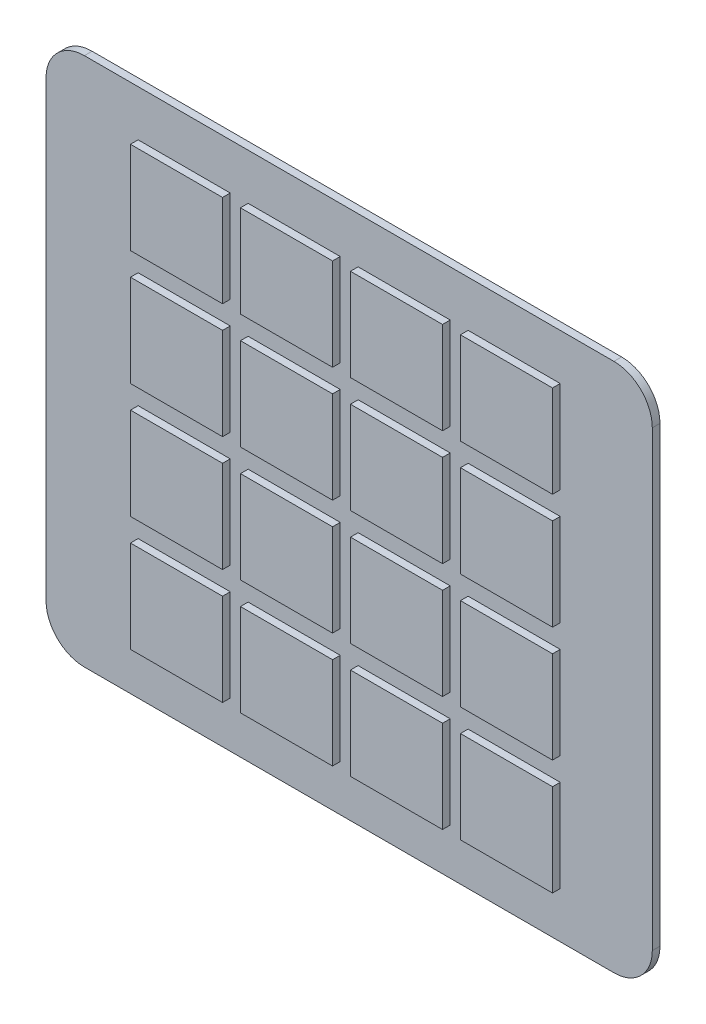
SolidWorks part; units mm, degrees
ref_plane "Plan de face" through (0, 0, 0) normal (0, 0, 1) x (1, 0, 0)
ref_plane "Plan de dessus" through (0, 0, 0) normal (0, 1, 0) x (1, 0, 0)
ref_plane "Plan de droite" through (0, 0, 0) normal (1, 0, 0) x (0, 0, -1)
sketch "Esquisse1" plane through (0, 0, 0) normal (0, 0, 1) x (1, 0, 0)
  line L0 (0, 6.4) -> (0, 5.9) construction
  line L1 (0, -0.5) -> (6.9, -0.5)
  line L2 (-0.5, 0) -> (-0.5, 5.9)
  line L3 (0, 6.4) -> (6.9, 6.4)
  line L4 (7.4, 0) -> (7.4, 5.9)
  line L5 (0, 5.9) -> (-0.5, 5.9) construction
  line L6 (3.45, 6.4) -> (3.45, -0.5) construction
  line L7 (-0.5, 2.95) -> (7.4, 2.95) construction
  arc A0 (0, 6.4) -> (-0.5, 5.9) centre (0, 5.9) ccw
  arc A1 (6.9, 6.4) -> (7.4, 5.9) centre (6.9, 5.9) cw
  arc A2 (6.9, -0.5) -> (7.4, 0) centre (6.9, 0) ccw
  arc A3 (0, -0.5) -> (-0.5, 0) centre (0, 0) cw
  dimension "D3" = 1
  dimension "D4" = 6.9
  dimension "D1" = 7.9
  dimension "D2" = 6.9
  dimension "D5" = 5.9
extrude "Boss.-Extru.1" add sketch "Esquisse1" along normal blind 0.1 contours L3 A1 L4 A2 L1 A3 L2 A0
sketch "Esquisse2" plane through (0, 0, 0.1) normal (0, 0, 1) x (1, 0, 0)
  line L0 (0, -0.5) -> (6.9, -0.5) construction
  line L1 (0.7, 1.3) -> (1.9, 1.3)
  line L2 (0.7, 1.3) -> (0.7, 0.1)
  line L3 (0.7, 0.1) -> (1.9, 0.1)
  line L4 (1.9, 1.3) -> (1.9, 0.1)
  line L5 (-0.5, 0) -> (-0.5, 5.9) construction
  line L6 (2.1333, 1.3) -> (2.1333, 0.1)
  line L7 (2.1333, 1.3) -> (3.3333, 1.3)
  line L8 (3.3333, 1.3) -> (3.3333, 0.1)
  line L9 (2.1333, 0.1) -> (3.3333, 0.1)
  line L10 (3.5667, 1.3) -> (3.5667, 0.1)
  line L11 (3.5667, 1.3) -> (4.7667, 1.3)
  line L12 (4.7667, 1.3) -> (4.7667, 0.1)
  line L13 (3.5667, 0.1) -> (4.7667, 0.1)
  line L14 (5, 1.3) -> (5, 0.1)
  line L15 (5, 1.3) -> (6.2, 1.3)
  line L16 (6.2, 1.3) -> (6.2, 0.1)
  line L17 (5, 0.1) -> (6.2, 0.1)
  line L18 (2.1333, 2.8) -> (2.1333, 1.6)
  line L19 (2.1333, 2.8) -> (3.3333, 2.8)
  line L20 (3.3333, 2.8) -> (3.3333, 1.6)
  line L21 (2.1333, 1.6) -> (3.3333, 1.6)
  line L22 (3.5667, 2.8) -> (3.5667, 1.6)
  line L23 (3.5667, 2.8) -> (4.7667, 2.8)
  line L24 (4.7667, 2.8) -> (4.7667, 1.6)
  line L25 (3.5667, 1.6) -> (4.7667, 1.6)
  line L26 (5, 2.8) -> (5, 1.6)
  line L27 (5, 2.8) -> (6.2, 2.8)
  line L28 (6.2, 2.8) -> (6.2, 1.6)
  line L29 (5, 1.6) -> (6.2, 1.6)
  line L30 (2.1333, 4.3) -> (2.1333, 3.1)
  line L31 (2.1333, 4.3) -> (3.3333, 4.3)
  line L32 (3.3333, 4.3) -> (3.3333, 3.1)
  line L33 (2.1333, 3.1) -> (3.3333, 3.1)
  line L34 (3.5667, 4.3) -> (3.5667, 3.1)
  line L35 (3.5667, 4.3) -> (4.7667, 4.3)
  line L36 (4.7667, 4.3) -> (4.7667, 3.1)
  line L37 (3.5667, 3.1) -> (4.7667, 3.1)
  line L38 (5, 4.3) -> (5, 3.1)
  line L39 (5, 4.3) -> (6.2, 4.3)
  line L40 (6.2, 4.3) -> (6.2, 3.1)
  line L41 (5, 3.1) -> (6.2, 3.1)
  line L42 (2.1333, 5.8) -> (2.1333, 4.6)
  line L43 (2.1333, 5.8) -> (3.3333, 5.8)
  line L44 (3.3333, 5.8) -> (3.3333, 4.6)
  line L45 (2.1333, 4.6) -> (3.3333, 4.6)
  line L46 (3.5667, 5.8) -> (3.5667, 4.6)
  line L47 (3.5667, 5.8) -> (4.7667, 5.8)
  line L48 (4.7667, 5.8) -> (4.7667, 4.6)
  line L49 (3.5667, 4.6) -> (4.7667, 4.6)
  line L50 (5, 5.8) -> (5, 4.6)
  line L51 (5, 5.8) -> (6.2, 5.8)
  line L52 (6.2, 5.8) -> (6.2, 4.6)
  line L53 (5, 4.6) -> (6.2, 4.6)
  line L54 (0.7, 2.8) -> (0.7, 1.6)
  line L55 (0.7, 2.8) -> (1.9, 2.8)
  line L56 (1.9, 2.8) -> (1.9, 1.6)
  line L57 (0.7, 1.6) -> (1.9, 1.6)
  line L58 (0.7, 4.3) -> (0.7, 3.1)
  line L59 (0.7, 4.3) -> (1.9, 4.3)
  line L60 (1.9, 4.3) -> (1.9, 3.1)
  line L61 (0.7, 3.1) -> (1.9, 3.1)
  line L62 (0.7, 5.8) -> (0.7, 4.6)
  line L63 (0.7, 5.8) -> (1.9, 5.8)
  line L64 (1.9, 5.8) -> (1.9, 4.6)
  line L65 (0.7, 4.6) -> (1.9, 4.6)
  line L66 (7.4, 0) -> (7.4, 5.9) construction
  line L67 (1.9, 0.1) -> (1.9, -0.5) construction
  line L68 (1.9, 5.8) -> (1.9, 6.4) construction
  line L69 (0, 6.4) -> (6.9, 6.4) construction
  dimension "D1" = 1.2
  dimension "D2" = 1.2
  dimension "D4" = 1.2
  dimension "D7" = 0.3
  dimension "D8" = 1.2
  dimension "D9" = 1.2
  dimension "D5" = 4
  dimension "D6" = 4
extrude "Boss.-Extru.2" add sketch "Esquisse2" along normal blind 0.1
